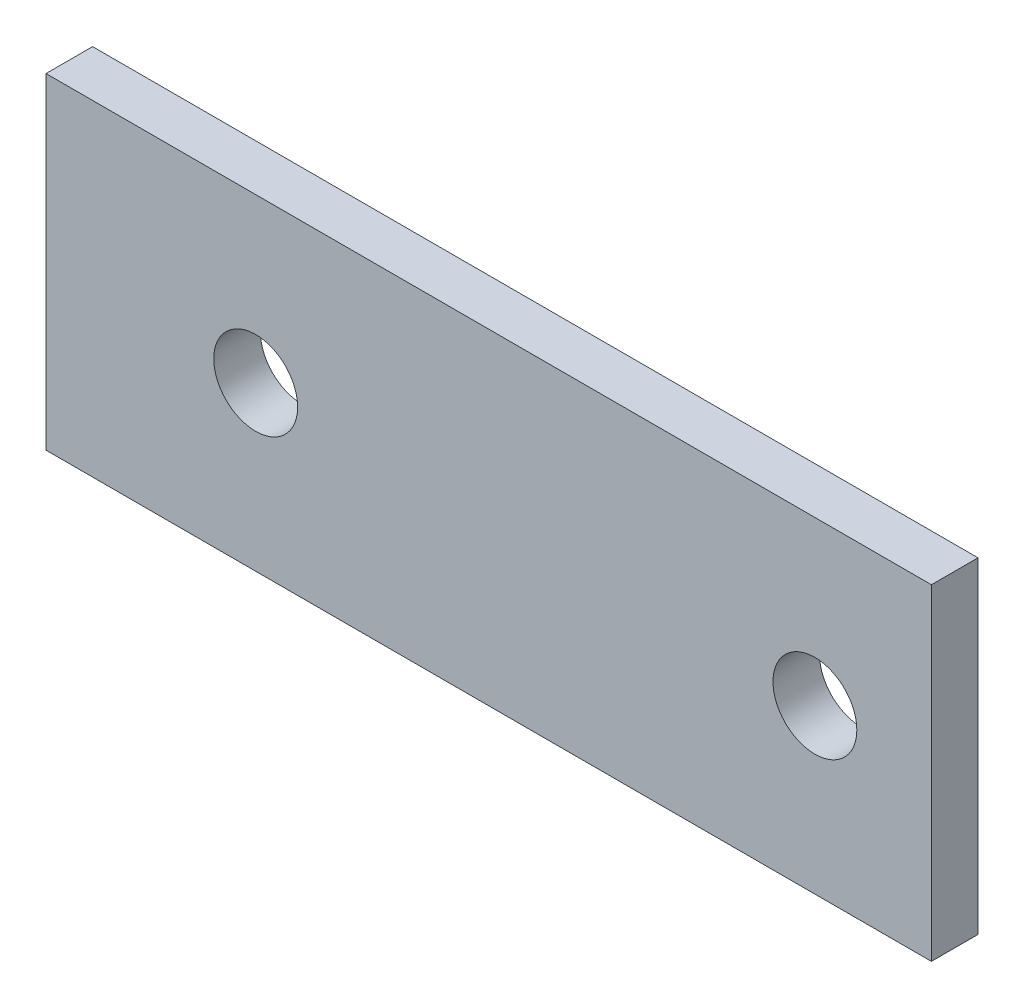
SolidWorks part; units mm, degrees
material "Plain Carbon Steel"
ref_plane "Front Plane" through (0, 0, 0) normal (0, 0, 1) x (1, 0, 0)
ref_plane "Top Plane" through (0, 0, 0) normal (0, 1, 0) x (1, 0, 0)
ref_plane "Right Plane" through (0, 0, 0) normal (1, 0, 0) x (0, 0, -1)
sketch "Sketch1" plane through (0, 0, 0) normal (0, 0, 1) x (1, 0, 0)
  line L1 (-95, 35) -> (95, 35)
  line L2 (-95, 35) -> (-95, -35)
  line L3 (-95, -35) -> (95, -35)
  line L4 (95, 35) -> (95, -35)
  line L5 (-95, 35) -> (95, -35) construction
  line L6 (-95, -35) -> (95, 35) construction
  circle A0 centre (70, 0) radius 9
  circle A1 centre (-50, 0) radius 9
  point P0 (0, 0)
  dimension "D3" = 25
  dimension "D4" = 18
  dimension "D5" = 120
  dimension "D6" = 18
  dimension "D1" = 70
  dimension "D2" = 190
extrude "Boss-Extrude1" add sketch "Sketch1" along normal mid plane 10
